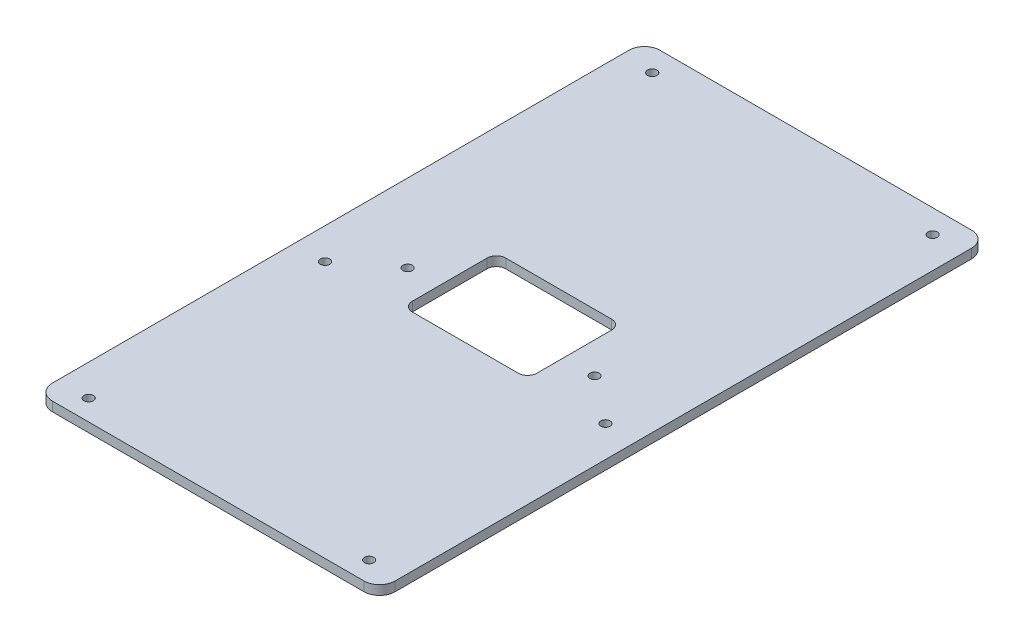
SolidWorks part; units mm, degrees
ref_plane "Alzado" through (0, 0, 0) normal (0, 0, 1) x (1, 0, 0)
ref_plane "Planta" through (0, 0, 0) normal (0, 1, 0) x (1, 0, 0)
ref_plane "Vista lateral" through (0, 0, 0) normal (1, 0, 0) x (0, 0, -1)
sketch "Croquis1" plane through (0, 0, 0) normal (0, 1, 0) x (1, 0, 0)
  line L1 (-55, -97.5) -> (55, -97.5)
  line L2 (-55, -97.5) -> (-55, 97.5)
  line L3 (-55, 97.5) -> (55, 97.5)
  line L4 (55, -97.5) -> (55, 97.5)
  line L5 (-55, -97.5) -> (55, 97.5) construction
  line L6 (-55, 97.5) -> (55, -97.5) construction
  point P0 (0, 0)
  dimension "D1" = 195
  dimension "D2" = 110
extrude "Saliente-Extruir1" add sketch "Croquis1" along normal blind 3
fillet "Redondeo1" radius 5 4 edges at (-55, 1.5, -97.5) (-55, 1.5, 97.5) (55, 1.5, -97.5) (55, 1.5, 97.5)
sketch "Croquis2" plane through (0, 3, 0) normal (0, 1, 0) x (1, 0, 0)
  circle A1 centre (-45, -90.8579) radius 1.5 construction
  circle A2 centre (-45, -15) radius 1.5 construction
  circle A3 centre (-45, 90) radius 1.5 construction
  circle A5 centre (45, 90) radius 1.5 construction
  circle A6 centre (45, -15) radius 1.5 construction
  circle A7 centre (45, -90.8579) radius 1.5 construction
  circle A9 centre (-45, -90.8579) radius 1.5
  circle A10 centre (-45, -15) radius 1.5
  circle A11 centre (-45, 90) radius 1.5
  circle A13 centre (45, 90) radius 1.5
  circle A14 centre (45, -15) radius 1.5
  circle A15 centre (45, -90.8579) radius 1.5
  circle A16 centre (-30, -3.5) radius 1.5 construction
  circle A17 centre (30, -3.5) radius 1.5 construction
  circle A18 centre (-30, -3.5) radius 1.5
  circle A19 centre (30, -3.5) radius 1.5
extrude "Cortar-Extruir1" cut sketch "Croquis2" against normal blind 3
sketch "Croquis3" plane through (0, 3, 0) normal (0, 1, 0) x (1, 0, 0)
  line L1 (-20, 15) -> (20, 15)
  line L2 (-20, 15) -> (-20, -15)
  line L3 (-20, -15) -> (20, -15)
  line L4 (20, 15) -> (20, -15)
  line L5 (-20, 15) -> (20, -15) construction
  line L6 (-20, -15) -> (20, 15) construction
  point P0 (0, 0)
  dimension "D1" = 40
  dimension "D2" = 30
extrude "Cortar-Extruir2" cut sketch "Croquis3" against normal blind 3
fillet "Redondeo2" radius 3 4 edges at (20, 1.5, 15) (-20, 1.5, 15) (20, 1.5, -15) (-20, 1.5, -15)
